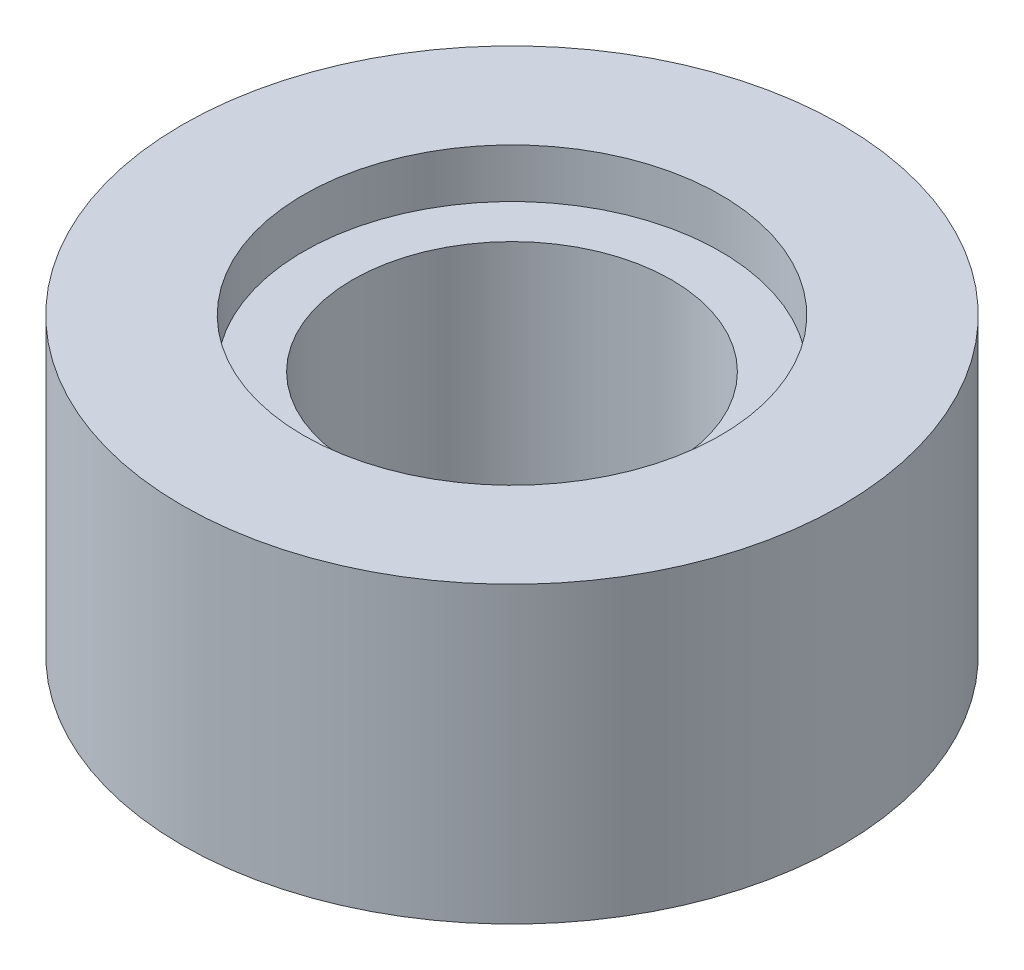
SolidWorks part; units mm, degrees
ref_plane "Front Plane" through (0, 0, 0) normal (0, 0, 1) x (1, 0, 0)
ref_plane "Top Plane" through (0, 0, 0) normal (0, 1, 0) x (1, 0, 0)
ref_plane "Right Plane" through (0, 0, 0) normal (1, 0, 0) x (0, 0, -1)
sketch "Sketch1" plane through (0, 0, 0) normal (0, 1, 0) x (1, 0, 0)
  circle A0 centre (0, 0) radius 6.5
  circle A1 centre (0, 0) radius 8.5
  dimension "D1" = 13
  dimension "D2" = 17
extrude "Boss-Extrude1" add sketch "Sketch1" along normal blind 10
sketch "Sketch2" plane through (0, 10, 0) normal (0, 1, 0) x (1, 0, 0)
  circle A0 centre (0, 0) radius 11.15
  circle A1 centre (0, 0) radius 8.5
  dimension "D1" = 22.3
extrude "Boss-Extrude2" add sketch "Sketch2" along normal blind 2 separate body
sketch "Sketch3" plane through (0, 12, 0) normal (0, 1, 0) x (1, 0, 0)
  circle A0 centre (0, 0) radius 11.15
  circle A1 centre (0, 0) radius 13.444
extrude "Boss-Extrude3" add sketch "Sketch3" against normal blind 12
